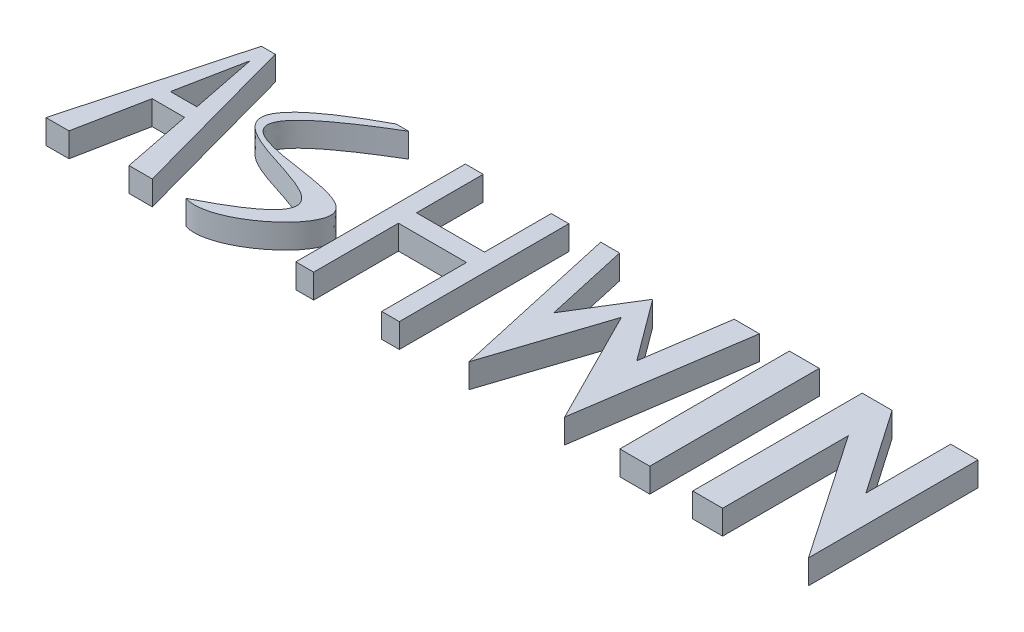
SolidWorks part; units mm, degrees
ref_plane "Front Plane" through (0, 0, 0) normal (0, 0, 1) x (1, 0, 0)
ref_plane "Top Plane" through (0, 0, 0) normal (0, 1, 0) x (1, 0, 0)
ref_plane "Right Plane" through (0, 0, 0) normal (1, 0, 0) x (0, 0, -1)
sketch "Sketch1" plane through (0, 0, 0) normal (0, 1, 0) x (1, 0, 0)
  line L0 (0, 0) -> (18.9666, 70.0205)
  line L1 (18.9666, 70.0205) -> (24.6825, 70.0205)
  line L2 (24.6825, 70.0205) -> (43.9089, 0)
  line L3 (43.9089, 0) -> (34.2957, 0)
  line L4 (34.2957, 0) -> (28.5693, 28.6921)
  line L5 (21.8246, 62.4858) -> (16.398, 35.0102)
  line L6 (9.4833, 0) -> (0, 0)
  line L7 (16.398, 35.0102) -> (27.3082, 35.0102)
  line L8 (15.1501, 28.6921) -> (9.4833, 0)
  line L9 (28.5693, 28.6921) -> (15.1501, 28.6921)
  line L10 (74.5619, 70.0205) -> (79.7894, 70.0205)
  line L11 (27.3082, 35.0102) -> (21.8246, 62.4858)
  line L12 (103.2081, 70.0205) -> (103.2081, 0)
  line L13 (103.2081, 0) -> (110.5772, 0)
  line L14 (110.5772, 0) -> (110.5772, 35.0102)
  line L15 (110.5772, 70.0205) -> (103.2081, 70.0205)
  line L16 (110.5772, 42.459) -> (138.6722, 42.459)
  line L17 (159.1209, 70.0205) -> (174.7054, 0)
  line L18 (138.6722, 35.0102) -> (110.5772, 35.0102)
  line L19 (138.6722, 42.459) -> (138.6722, 70.0205)
  line L20 (138.6722, 70.0205) -> (145.9496, 70.0205)
  line L21 (145.9496, 70.0205) -> (145.9496, 0)
  line L22 (145.9496, 0) -> (138.6722, 0)
  line L23 (138.6722, 0) -> (138.6722, 35.0102)
  line L24 (110.5772, 42.459) -> (110.5772, 70.0205)
  line L25 (174.7054, 0) -> (190.29, 47.4208)
  line L26 (190.29, 47.4208) -> (214.2515, 0)
  line L27 (214.2515, 0) -> (224.6834, 70.0205)
  line L28 (224.6834, 70.0205) -> (214.2515, 70.0205)
  line L29 (214.2515, 70.0205) -> (209.0355, 35.0102)
  line L30 (209.0355, 35.0102) -> (190.29, 60.3192)
  line L31 (190.29, 60.3192) -> (174.7054, 35.0102)
  line L32 (174.7054, 35.0102) -> (166.9131, 70.0205)
  line L33 (166.9131, 70.0205) -> (159.1209, 70.0205)
  line L34 (267.1378, 0) -> (267.1378, 70.0205)
  line L35 (237.0436, 70.0205) -> (249.4037, 70.0205)
  line L36 (237.0436, 70.0205) -> (237.0436, 0)
  line L37 (237.0436, 0) -> (249.4037, 0)
  line L38 (249.4037, 70.0205) -> (249.4037, 0)
  line L39 (279.498, 51.9253) -> (314.9663, 0)
  line L40 (314.9663, 0) -> (314.9663, 70.0205)
  line L41 (314.9663, 70.0205) -> (303.6809, 70.0205)
  line L42 (303.6809, 70.0205) -> (303.6809, 35.0102)
  line L43 (303.6809, 35.0102) -> (279.498, 70.0205)
  line L44 (279.498, 70.0205) -> (267.1378, 70.0205)
  line L45 (279.498, 51.9253) -> (279.498, 0)
  line L46 (279.498, 0) -> (267.1378, 0)
  spline S0 degree 3 poles (74.5619, 70.0205) (-18.9844, 19.6119) (142.6638, 42.7382) (57.7331, 0) knots 0 0 0 0 1 1 1 1
  spline S1 degree 3 poles (79.7894, 70.0205) (3.8123, 24.9115) (138.8105, 50.8241) (71.3213, -4.2875) (57.7331, 0) knots 0 0 0 0 0.628481 1 1 1 1
extrude "Boss-Extrude1" add sketch "Sketch1" along normal blind 10
